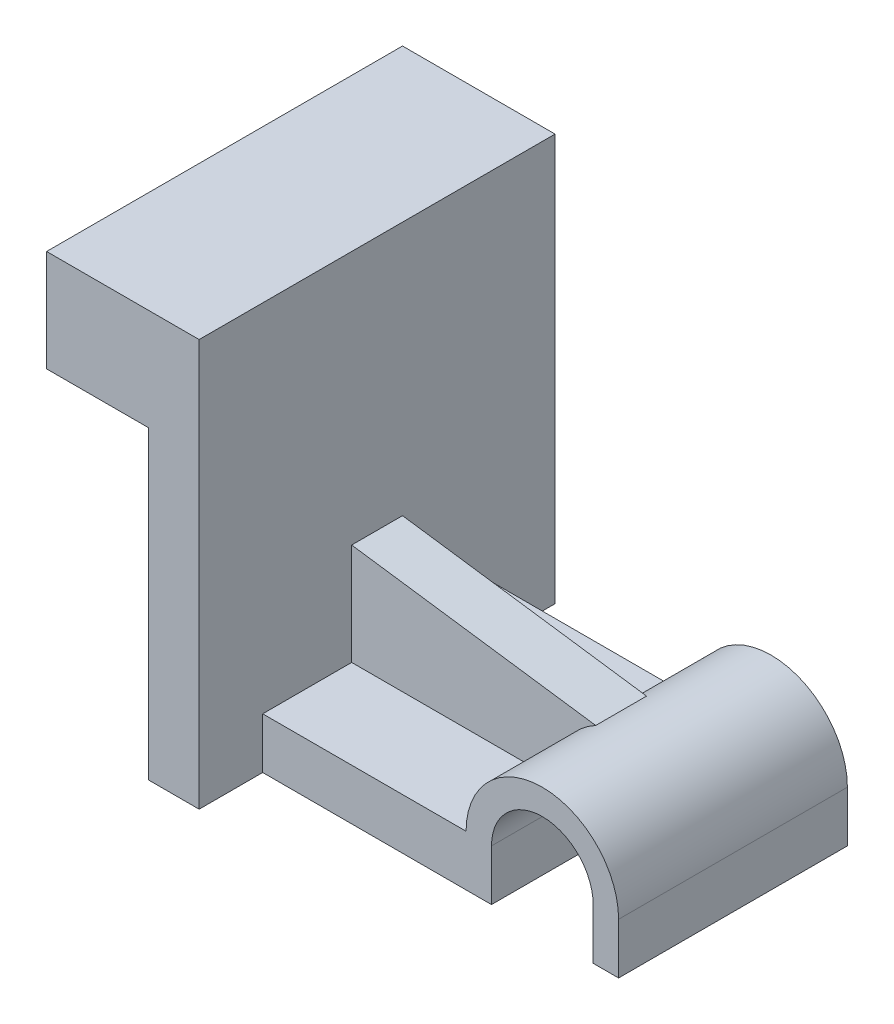
SolidWorks part; units mm, degrees
ref_plane "前基準面" through (0, 0, 0) normal (0, 0, 1) x (1, 0, 0)
ref_plane "上基準面" through (0, 0, 0) normal (0, 1, 0) x (1, 0, 0)
ref_plane "右基準面" through (0, 0, 0) normal (1, 0, 0) x (0, 0, -1)
sketch "草圖1" plane through (0, 0, 0) normal (0, 0, 1) x (1, 0, 0)
  line L0 (-15, 0) -> (-55, 0)
  line L1 (-10, 0) -> (-10, -10)
  line L2 (15, 0) -> (15, -10)
  line L3 (15, -10) -> (10, -10)
  line L4 (-55, 0) -> (-55, -10)
  line L5 (10, 0) -> (10, -10)
  line L6 (-10, -10) -> (-55, -10)
  arc A0 (15, 0) -> (-15, 0) centre (0, 0) ccw
  arc A1 (10, 0) -> (-10, 0) centre (0, 0) ccw
  dimension "D1" = 20
  dimension "D2" = 30
  dimension "D3" = 10
  dimension "D4" = 70
extrude "填料-伸長1" add sketch "草圖1" against normal blind 45 contours A0 L0 L4 L6 L1 A1 L5 L3 L2
sketch "草圖2" plane through (-55, 0, 0) normal (-1, 0, 0) x (0, 0, 1)
  line L0 (-45, -10) -> (0, -10) construction
  line L1 (-57.5, 70) -> (12.5, 70)
  line L2 (-57.5, 70) -> (-57.5, -10)
  line L3 (-57.5, -10) -> (12.5, -10)
  line L4 (12.5, 70) -> (12.5, -10)
  line L5 (-22.5, 25.2638) -> (-22.5, -47.1605) construction
  line L9 (0, -10) -> (0, 0)
  line L10 (0, 0) -> (-45, 0)
  line L11 (-45, 0) -> (-45, -10)
  line L12 (-45, -10) -> (0, -10)
  line L16 (-45, -10) -> (0, -10)
  dimension "D1" = 70
  dimension "D2" = 80
  dimension "D3" = 0
extrude "填料-伸長2" add sketch "草圖2" along normal blind 30 contours L1 L4 L3 L2
sketch "草圖3" plane through (-85, 0, 0) normal (-1, 0, 0) x (0, 0, 1)
  line L0 (-57.5, 70) -> (-57.5, -10) construction
  line L1 (-57.5, 50) -> (12.5, 50)
  line L2 (-57.5, 50) -> (-57.5, -10)
  line L3 (-57.5, -10) -> (12.5, -10)
  line L4 (12.5, 50) -> (12.5, -10)
  line L5 (-57.5, 70) -> (12.5, 70) construction
  dimension "D1" = 20
extrude "除料-伸長1" cut sketch "草圖3" against normal blind 20
sketch "草圖4" plane through (-55, 0, 0) normal (1, 0, 0) x (0, 0, -1)
  line L0 (45, 0) -> (0, 0) construction
  line L1 (17.5, 0) -> (27.5, 0)
  line L2 (17.5, 0) -> (17.5, 20)
  line L3 (17.5, 20) -> (27.5, 20)
  line L4 (27.5, 0) -> (27.5, 20)
  line L5 (22.5, 21.1348) -> (22.5, -18.0599) construction
  dimension "D1" = 20
  dimension "D2" = 10
extrude "填料-伸長4" add sketch "草圖4" along normal blind 48
sketch "草圖6" plane through (0, 0, 0) normal (0, 0, 1) x (1, 0, 0)
  line L0 (10, 0) -> (10, -10) construction
  line L1 (-10, 0) -> (-10, -10) construction
  line L2 (10, 0) -> (10, -10)
  line L3 (-10, 0) -> (-10, -10)
  line L4 (-10, -10) -> (10, -10)
  arc A0 (10, 0) -> (-10, 0) centre (0, 0) ccw construction
  arc A1 (10, 0) -> (-10, 0) centre (0, 0) ccw
extrude "除料-伸長2" cut sketch "草圖6" against normal through all
sketch "草圖7" plane through (0, 0, -17.5) normal (0, 0, 1) x (1, 0, 0)
  line L0 (-7, 13.2665) -> (-55, 20)
  line L1 (-55, 20) -> (-7, 20)
  line L2 (-7, 20) -> (-7, 13.2665)
extrude "除料-伸長3" cut sketch "草圖7" against normal through all
